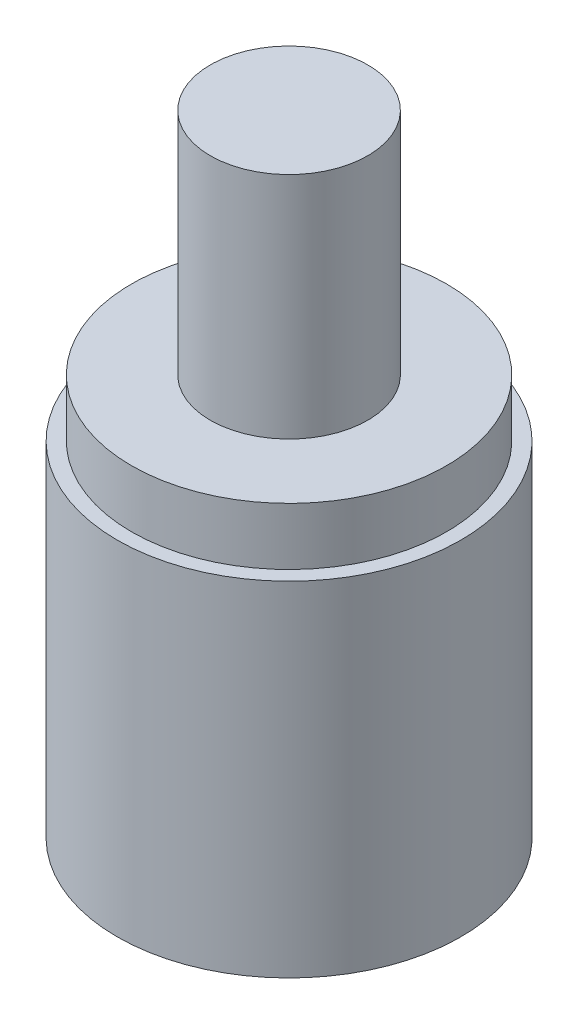
SolidWorks part; units mm, degrees
ref_plane "前视基准面" through (0, 0, 0) normal (0, 0, 1) x (1, 0, 0)
ref_plane "上视基准面" through (0, 0, 0) normal (0, 1, 0) x (1, 0, 0)
ref_plane "右视基准面" through (0, 0, 0) normal (1, 0, 0) x (0, 0, -1)
sketch "草图1" plane through (0, 0, 0) normal (0, 1, 0) x (1, 0, 0)
  circle A0 centre (0, 0) radius 4.75
  circle A1 centre (0, 0) radius 6
  dimension "D1" = 9.5
  dimension "D2" = 12
extrude "凸台-拉伸1" add sketch "草图1" along normal blind 12 contours A0 | A1
sketch "草图2" plane through (0, 12, 0) normal (0, 1, 0) x (1, 0, 0)
  circle A0 centre (0, 0) radius 5.5
  dimension "D1" = 11
extrude "凸台-拉伸2" add sketch "草图2" along normal blind 2 contours A0
sketch "草图3" plane through (0, 14, 0) normal (0, 1, 0) x (1, 0, 0)
  circle A0 centre (0, 0) radius 2.75
  dimension "D1" = 5.5
extrude "凸台-拉伸3" add sketch "草图3" along normal blind 8 contours A0
sketch "草图4" plane through (0, 22, 0) normal (0, 1, 0) x (1, 0, 0)
  circle A0 centre (0, 0) radius 5
  dimension "D1" = 10
